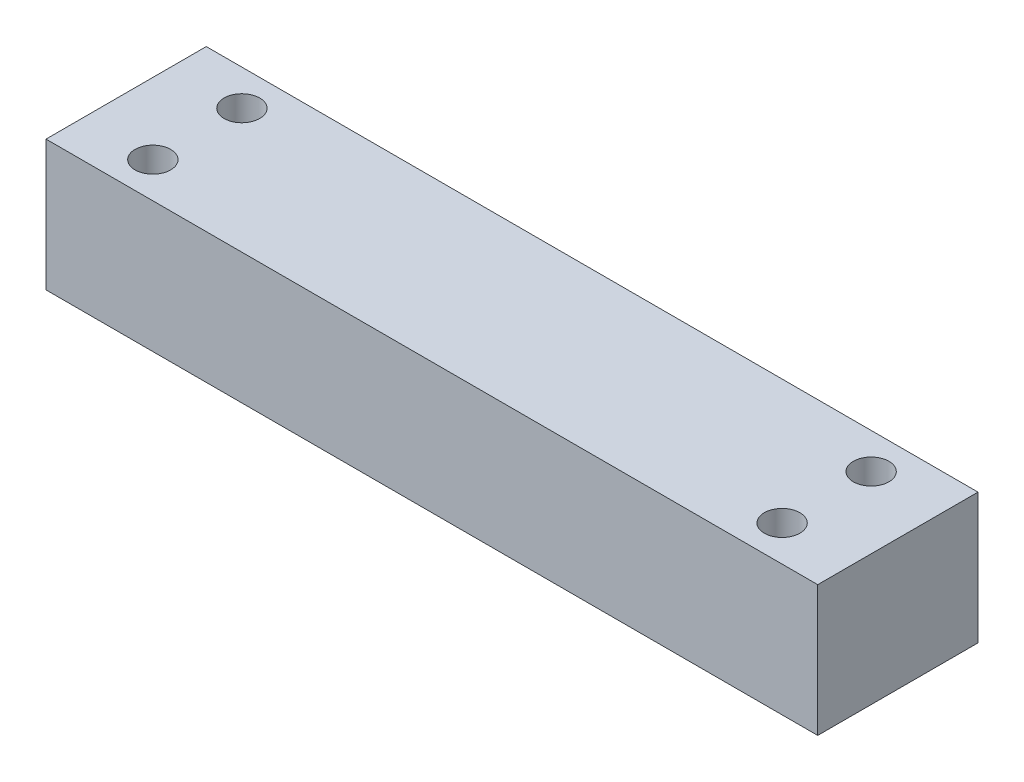
SolidWorks part; units mm, degrees
ref_plane "Front Plane" through (0, 0, 0) normal (0, 0, 1) x (1, 0, 0)
ref_plane "Top Plane" through (0, 0, 0) normal (0, 1, 0) x (1, 0, 0)
ref_plane "Right Plane" through (0, 0, 0) normal (1, 0, 0) x (0, 0, -1)
sketch "Sketch1" plane through (0, 0, 0) normal (0, 1, 0) x (1, 0, 0)
  line L0 (-65, 0) -> (65, 0) construction
  line L1 (-65, 13.5) -> (65, 13.5)
  line L2 (-65, 13.5) -> (-65, -13.5)
  line L3 (-65, -13.5) -> (65, -13.5)
  line L4 (65, 13.5) -> (65, -13.5)
  circle A0 centre (53, 7.5) radius 3
  circle A1 centre (53, -7.5) radius 3
  circle A2 centre (-53, 7.5) radius 3
  circle A3 centre (-53, -7.5) radius 3
  point P4 (0, 13.5)
  point P7 (65, 0)
  dimension "D3" = 6
  dimension "D4" = 6
  dimension "D1" = 130
  dimension "D2" = 27
  dimension "D5" = 15
  dimension "D6" = 7.5
  dimension "D7" = 12
  dimension "D9" = 12
  dimension "D10" = 7.5
  dimension "D8" = 2
extrude "Boss-Extrude1" add sketch "Sketch1" along normal blind 22
